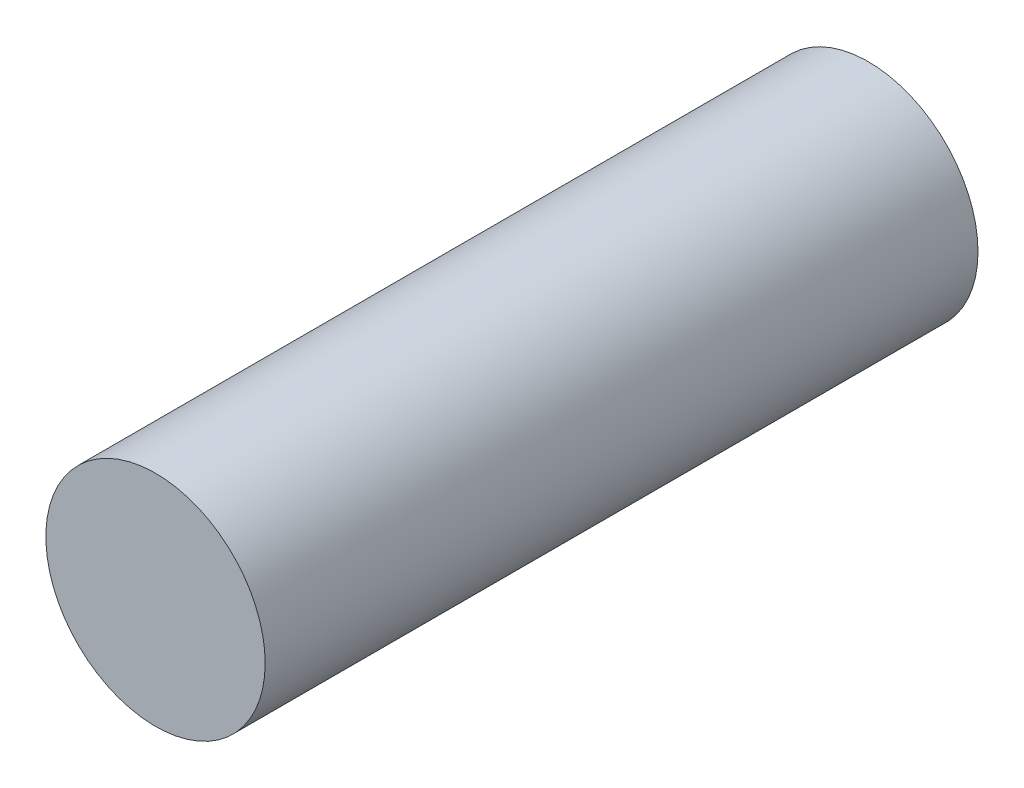
SolidWorks part; units mm, degrees
ref_plane "前视基准面" through (0, 0, 0) normal (0, 0, 1) x (1, 0, 0)
ref_plane "上视基准面" through (0, 0, 0) normal (0, 1, 0) x (1, 0, 0)
ref_plane "右视基准面" through (0, 0, 0) normal (1, 0, 0) x (0, 0, -1)
sketch "草图1" plane through (0, 0, 0) normal (0, 0, 1) x (1, 0, 0)
  circle A0 centre (0, 0) radius 10
extrude "凸台-拉伸1" add sketch "草图1" along normal blind 65
